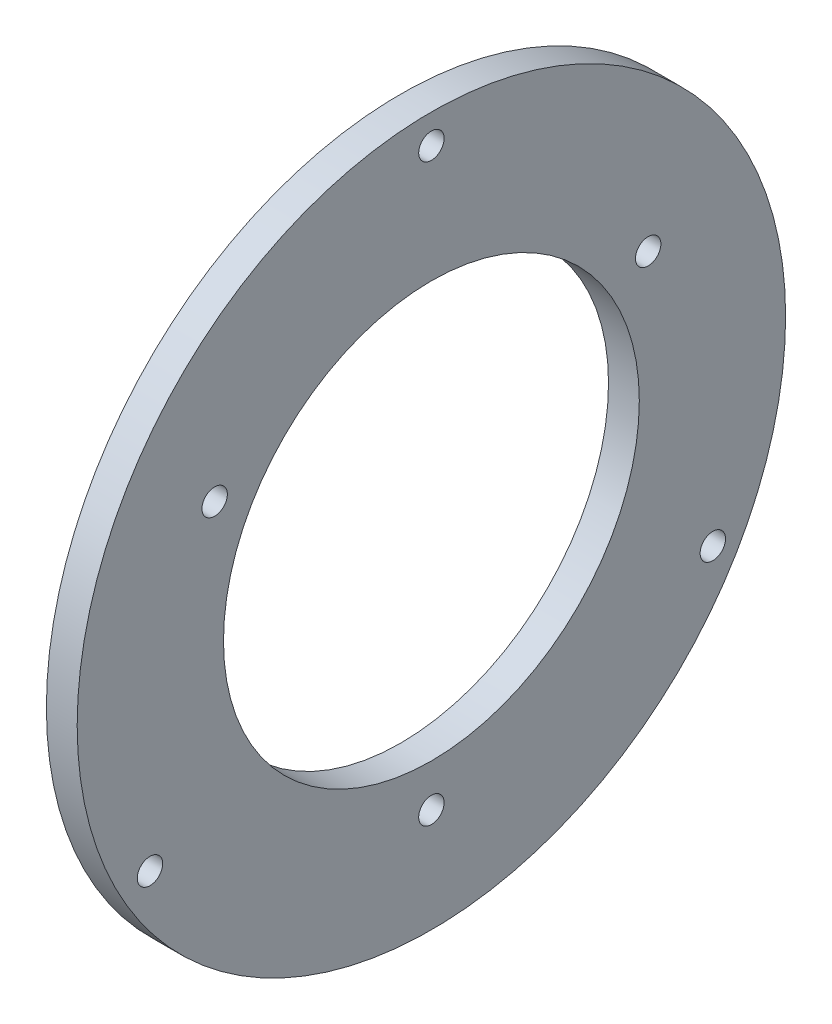
SolidWorks part; units mm, degrees
material "AISI 304"
ref_plane "Front Plane" through (0, 0, 0) normal (0, 0, 1) x (1, 0, 0)
ref_plane "Top Plane" through (0, 0, 0) normal (0, 1, 0) x (1, 0, 0)
ref_plane "Right Plane" through (0, 0, 0) normal (1, 0, 0) x (0, 0, -1)
sketch "Axial profile (mm)" plane through (0, 0, 0) normal (0, 0, 1) x (1, 0, 0)
  line L0 (-110, 0) -> (75, 0) construction
  line L1 (131.7, 27) -> (135.7, 27)
  line L2 (135.7, 27) -> (135.7, 46)
  line L3 (135.7, 46) -> (131.7, 46)
  line L4 (131.7, 46) -> (131.7, 27)
revolve "Full revolution" add sketch "Axial profile (mm)" angle 360 about L0
sketch "Sketch2" plane through (0, 0, 0) normal (1, 0, 0) x (0, 0, -1)
  circle A0 centre (0, 42.2) radius 1.65
  circle A1 centre (-36.5463, -21.1) radius 1.65
  circle A2 centre (36.5463, -21.1) radius 1.65
  circle A3 centre (-28.1458, 16.25) radius 1.65
  circle A4 centre (0, -32.5) radius 1.65
  circle A5 centre (28.1458, 16.25) radius 1.65
extrude "Axial holes" cut sketch "Sketch2" along normal through all and the other way through all
